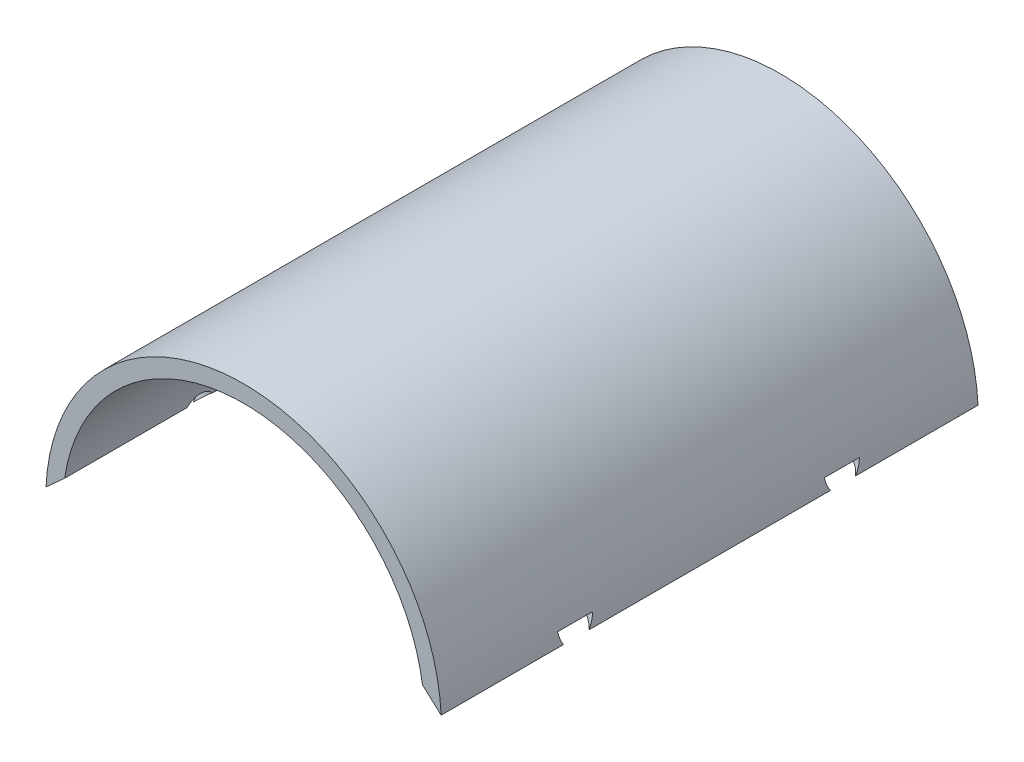
SolidWorks part; units mm, degrees
ref_plane "Front Plane" through (0, 0, 0) normal (0, 0, 1) x (1, 0, 0)
ref_plane "Top Plane" through (0, 0, 0) normal (0, 1, 0) x (1, 0, 0)
ref_plane "Right Plane" through (0, 0, 0) normal (1, 0, 0) x (0, 0, -1)
sketch "Sketch1" plane through (0, 0, 0) normal (0, 0, 1) x (1, 0, 0)
  line L0 (0, 0) -> (0, 44.45) construction
  line L1 (-40.2039, 5.9378) -> (40.2039, 5.9378) construction
  line L2 (-44.399, 2.1278) -> (44.399, 2.1278) construction
  line L3 (-40.2039, 5.9378) -> (-44.399, 2.1278)
  line L4 (40.2039, 5.9378) -> (44.399, 2.1278)
  arc A0 (44.399, 2.1278) -> (-44.399, 2.1278) centre (0, 0) ccw
  arc A1 (40.2039, 5.9378) -> (-40.2039, 5.9378) centre (0, 0) ccw
  dimension "D1" = 88.9
  dimension "D2" = 3.81
  dimension "D3" = 3.81
extrude "Boss-Extrude1" add sketch "Sketch1" along normal blind 120.65
sketch "Sketch2" plane through (-21.1272, 23.263, 0) normal (0.6723, -0.7403, 0) x (0.7403, 0.6723, 0)
  line L0 (-28.6033, 120.65) -> (-28.6033, 0.1046) construction
  line L1 (-31.4368, 120.65) -> (-25.7698, 120.65) construction
  line L2 (-31.4368, 60.325) -> (-25.7698, 60.325) construction
  line L3 (-31.4368, 120.65) -> (-31.4368, 0) construction
  line L4 (-25.7698, 120.65) -> (-25.7698, 0) construction
  circle A0 centre (-28.6033, 90.3493) radius 4
  circle A1 centre (-28.6033, 30.3007) radius 4
  point P12 (-28.6033, 60.3773)
  dimension "D1" = 8
  dimension "D2" = 29.972
extrude "Cut-Extrude1" cut sketch "Sketch2" against normal blind 2
sketch "Sketch3" plane through (21.1272, 23.263, 0) normal (-0.6723, -0.7403, 0) x (0.7403, -0.6723, 0)
  line L0 (28.6033, 120.65) -> (28.6033, 0) construction
  line L1 (25.7698, 120.65) -> (31.4368, 120.65) construction
  line L2 (25.7698, 0) -> (31.4368, 0) construction
  line L3 (25.7698, 60.325) -> (31.4368, 60.325) construction
  line L4 (25.7698, 120.65) -> (25.7698, 0) construction
  line L5 (31.4368, 120.65) -> (31.4368, 0) construction
  circle A0 centre (28.6033, 90.297) radius 4
  circle A1 centre (28.6033, 30.353) radius 4
  dimension "D1" = 8
  dimension "D2" = 29.972
extrude "Cut-Extrude2" cut sketch "Sketch3" against normal blind 2
